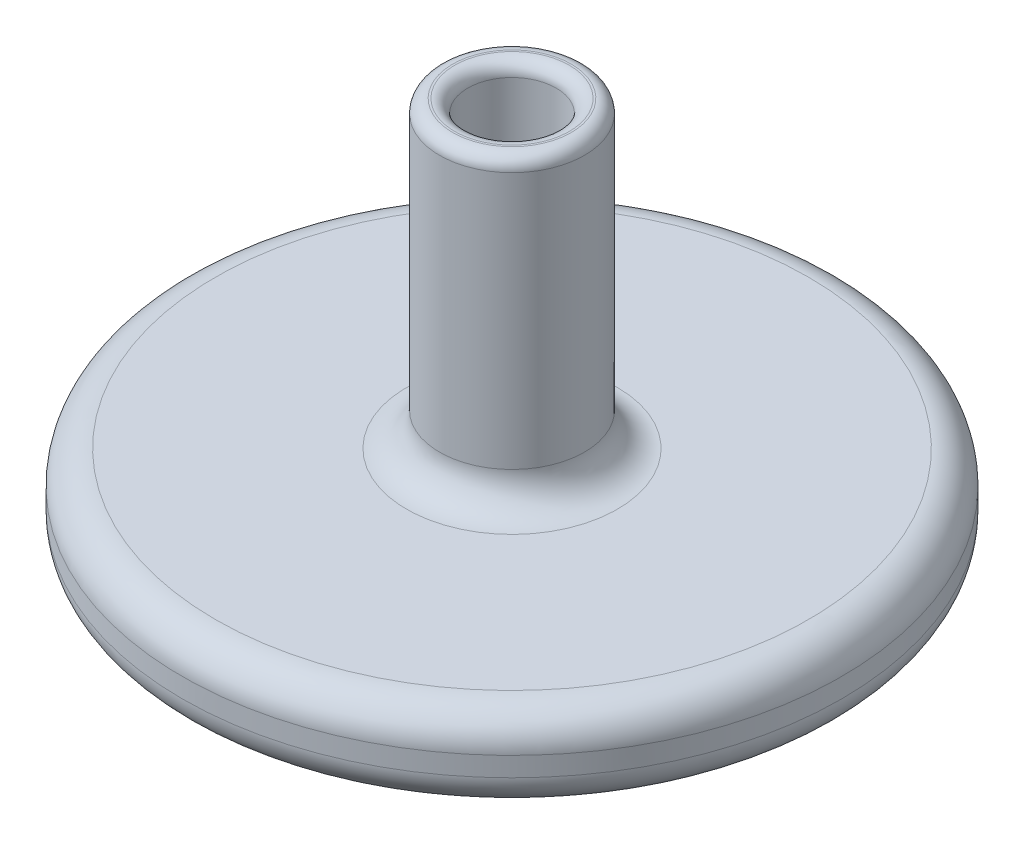
SolidWorks part; units mm, degrees
material "Brass"
ref_plane "Front Plane" through (0, 0, 0) normal (0, 0, 1) x (1, 0, 0)
ref_plane "Top Plane" through (0, 0, 0) normal (0, 1, 0) x (1, 0, 0)
ref_plane "Right Plane" through (0, 0, 0) normal (1, 0, 0) x (0, 0, -1)
sketch "Sketch1" plane through (0, 0, 0) normal (0, 0, 1) x (1, 0, 0)
  line L0 (0, 0) -> (0, 55.9963) construction
  line L1 (-0.8509, 8.0518) -> (-0.8509, 2.2098)
  line L2 (-0.8509, 2.2098) -> (0, 2.2098)
  line L3 (0, 2.2098) -> (0, 0)
  line L4 (-0.8509, 8.0518) -> (-1.397, 8.0518)
  line L5 (-1.397, 8.0518) -> (-1.397, 2.2098)
  line L6 (-1.397, 2.2098) -> (-6.35, 2.2098)
  line L7 (-6.35, 2.2098) -> (-6.35, 0.6858)
  line L8 (0, 0) -> (7.3439, 0) construction
  arc A0 (0, 0) -> (-6.35, 0.6858) centre (0, 29.741) cw
  dimension "D1" = 8.0518
  dimension "D2" = 1.7018
  dimension "D3" = 2.794
  dimension "D4" = 1.524
  dimension "D5" = 5.842
  dimension "D6" = 12.7
revolve "Revolve1" add sketch "Sketch1" angle 360 about L0
fillet "Fillet1" radius 0.635 3 edges at (0, 0.6858, -6.35) (0, 2.2098, -6.35) (0, 2.2098, -1.397)
fillet "Fillet2" radius 0.254 2 edges at (0, 8.0518, -0.8509) (0, 8.0518, -1.397)
